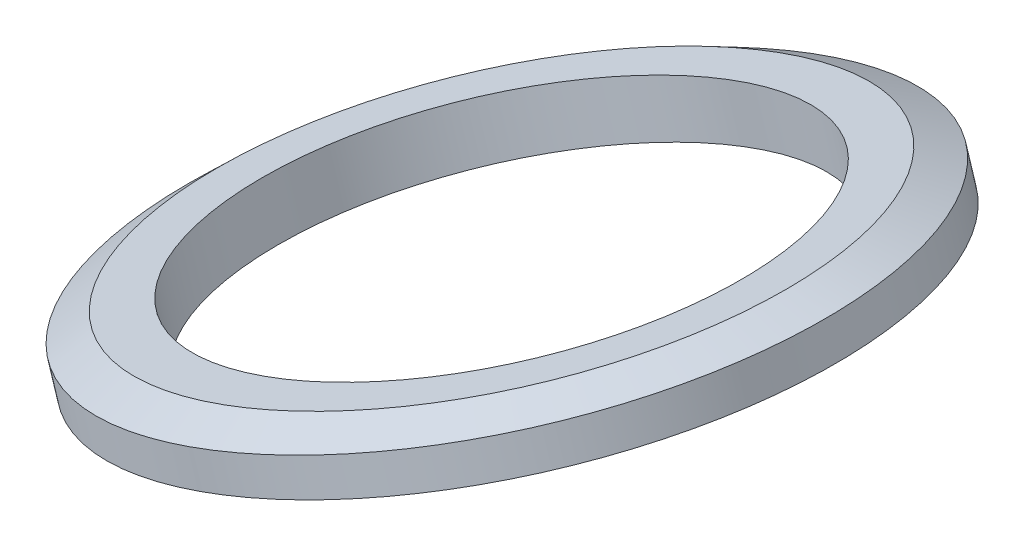
SolidWorks part; units mm, degrees
material "Acero aleado"
ref_plane "Alzado" through (0, 0, 0) normal (0, 0, 1) x (1, 0, 0)
ref_plane "Planta" through (0, 0, 0) normal (0, 1, 0) x (1, 0, 0)
ref_plane "Vista lateral" through (0, 0, 0) normal (1, 0, 0) x (0, 0, -1)
sketch "Sk_Cono" plane through (0, 0, 0) normal (0, 0, 1) x (1, 0, 0)
  line L0 (422.136, 400.5414) -> (424.711, 401.3533)
  line L1 (424.711, 401.3533) -> (426.9191, 401.001)
  line L2 (426.9191, 401.001) -> (427.5206, 399.0936)
  line L3 (427.5206, 399.0936) -> (423.0381, 397.6802)
  line L4 (423.0381, 397.6802) -> (422.136, 400.5414)
  line L5 (406.9943, 401.0097) -> (417.5193, 367.6297) construction
revolve "Cono" add sketch "Sk_Cono" angle 360 about L5
